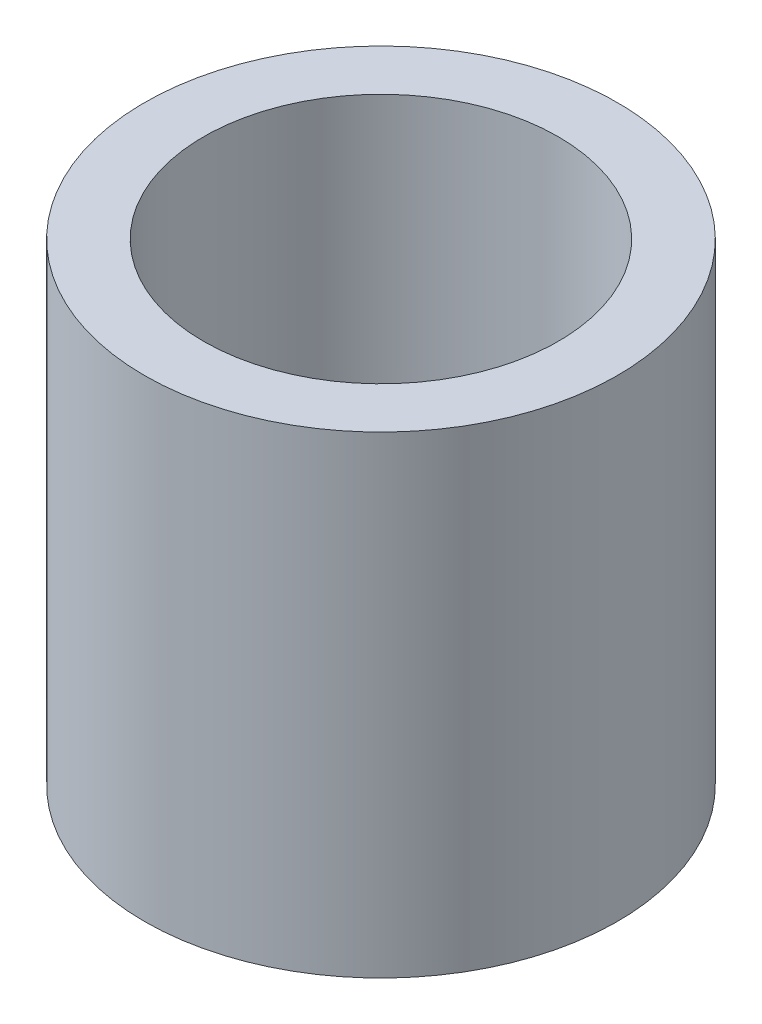
SolidWorks part; units mm, degrees
ref_plane "Front" through (0, 0, 0) normal (0, 0, 1) x (1, 0, 0)
ref_plane "Top" through (0, 0, 0) normal (0, 1, 0) x (1, 0, 0)
ref_plane "Right" through (0, 0, 0) normal (1, 0, 0) x (0, 0, -1)
sketch "Sketch1" plane through (0, 0, 0) normal (0, 1, 0) x (1, 0, 0)
  circle A0 centre (0, 0) radius 4
  circle A1 centre (0, 0) radius 3
extrude "Boss-Extrude1" add sketch "Sketch1" along normal blind 8
